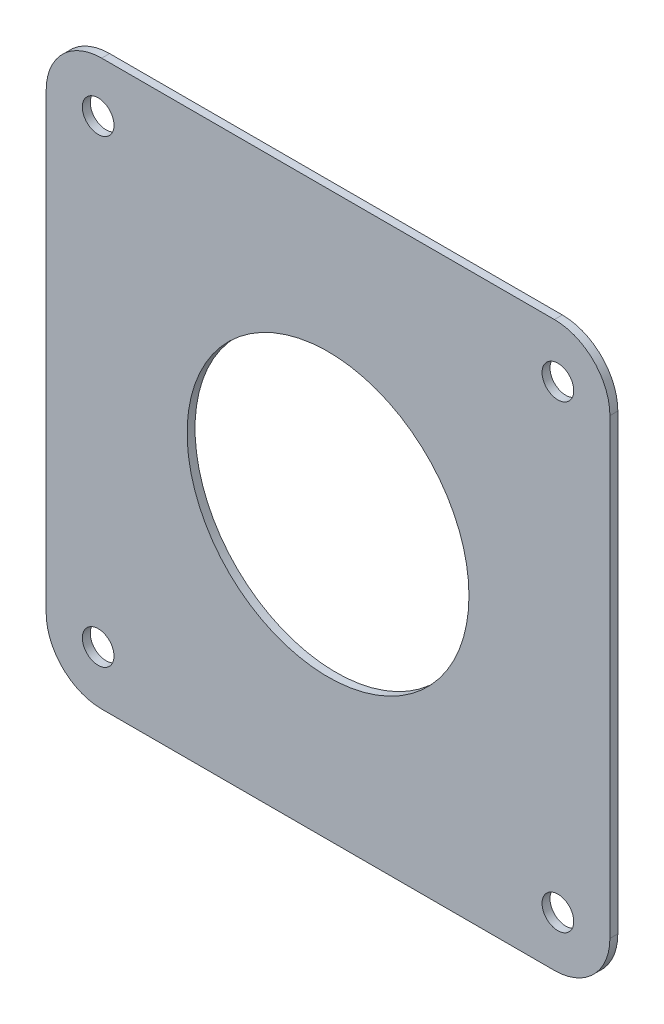
SolidWorks part; units mm, degrees
ref_plane "Front Plane" through (0, 0, 0) normal (1, 0, 0) x (0, 1, 0)
ref_plane "Top Plane" through (0, 0, 0) normal (0, 0, 1) x (0, 1, 0)
ref_plane "Right Plane" through (0, 0, 0) normal (0, 1, 0) x (-1, 0, 0)
sketch "Sketch1" plane through (0, 0, 0) normal (0, 0, 1) x (0, 1, 0)
  line L1 (-28.56, -35.56) -> (28.56, -35.56)
  line L2 (-35.56, -28.56) -> (-35.56, 28.56)
  line L3 (-28.56, 35.56) -> (28.56, 35.56)
  line L4 (35.56, -28.56) -> (35.56, 28.56)
  line L5 (-35.56, -35.56) -> (35.56, 35.56) construction
  line L6 (-35.56, 35.56) -> (35.56, -35.56) construction
  circle A0 centre (0, 0) radius 17.78
  circle A1 centre (-29, 29) radius 2
  circle A2 centre (29, -29) radius 2
  circle A3 centre (29, 29) radius 2
  circle A4 centre (-29, -29) radius 2
  arc A5 (-28.56, -35.56) -> (-35.56, -28.56) centre (-28.56, -28.56) cw
  arc A6 (28.56, 35.56) -> (35.56, 28.56) centre (28.56, 28.56) cw
  arc A7 (28.56, -35.56) -> (35.56, -28.56) centre (28.56, -28.56) ccw
  arc A8 (-35.56, 28.56) -> (-28.56, 35.56) centre (-28.56, 28.56) cw
  point P0 (0, 0)
  dimension "D2" = 35.56
  dimension "D3" = 4
  dimension "D4" = 58
  dimension "D5" = 7
  dimension "D1" = 71.12
extrude "Boss-Extrude1" add sketch "Sketch1" along normal blind 1
